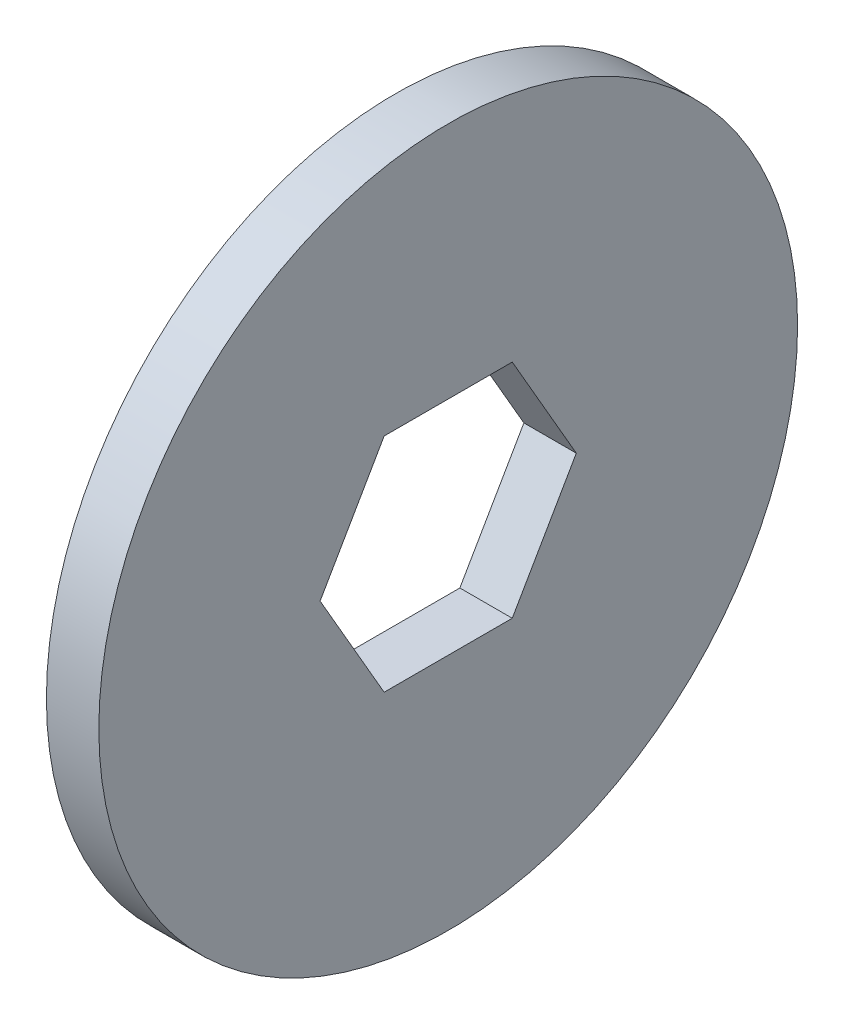
SolidWorks part; units mm, degrees
ref_plane "Alzado" through (0, 0, 0) normal (0, 0, 1) x (1, 0, 0)
ref_plane "Planta" through (0, 0, 0) normal (0, 1, 0) x (1, 0, 0)
ref_plane "Vista lateral" through (0, 0, 0) normal (1, 0, 0) x (0, 0, -1)
sketch "Croquis1" plane through (0, 0, 0) normal (1, 0, 0) x (0, 0, -1)
  line L1 (7.3323, 0) -> (3.6662, 6.35)
  line L2 (3.6662, 6.35) -> (-3.6662, 6.35)
  line L3 (-3.6662, 6.35) -> (-7.3323, 0)
  line L4 (-7.3323, 0) -> (-3.6662, -6.35)
  line L5 (-3.6662, -6.35) -> (3.6662, -6.35)
  line L6 (3.6662, -6.35) -> (7.3323, 0)
  circle A0 centre (0, 0) radius 20
  circle A1 centre (0, 0) radius 6.35 construction
  dimension "D1" = 40
  dimension "D2" = 12.7
extrude "Saliente-Extruir1" add sketch "Croquis1" along normal blind 3
